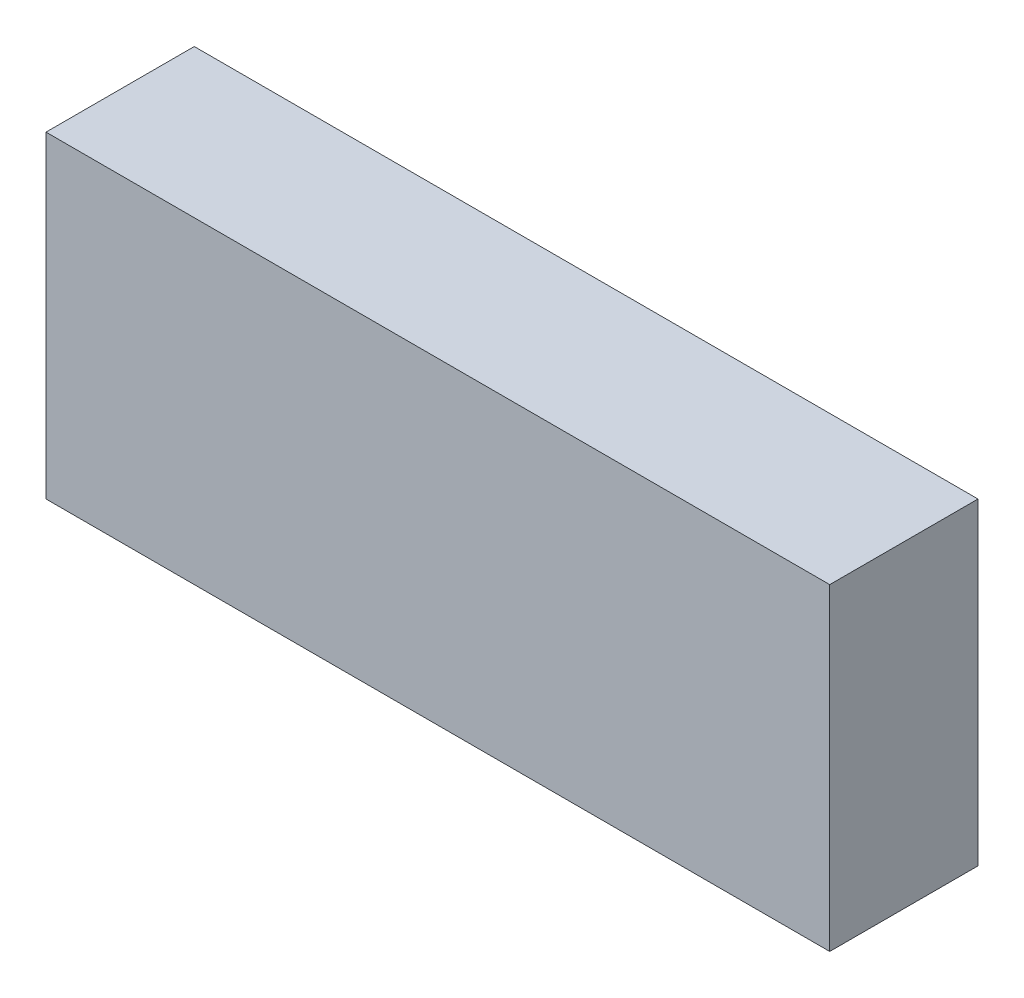
SolidWorks part; units mm, degrees
ref_plane "Alzado" through (0, 0, 0) normal (0, 0, 1) x (1, 0, 0)
ref_plane "Planta" through (0, 0, 0) normal (0, 1, 0) x (1, 0, 0)
ref_plane "Vista lateral" through (0, 0, 0) normal (1, 0, 0) x (0, 0, -1)
sketch "Sketch1" plane through (0, 0, 0) normal (0, 0, 1) x (1, 0, 0)
  line L1 (0, 0) -> (37, 0)
  line L2 (0, 0) -> (0, 15)
  line L3 (0, 15) -> (37, 15)
  line L4 (37, 0) -> (37, 15)
  dimension "D1" = 37
  dimension "D2" = 15
extrude "Boss-Extrude1" add sketch "Sketch1" along normal blind 7
